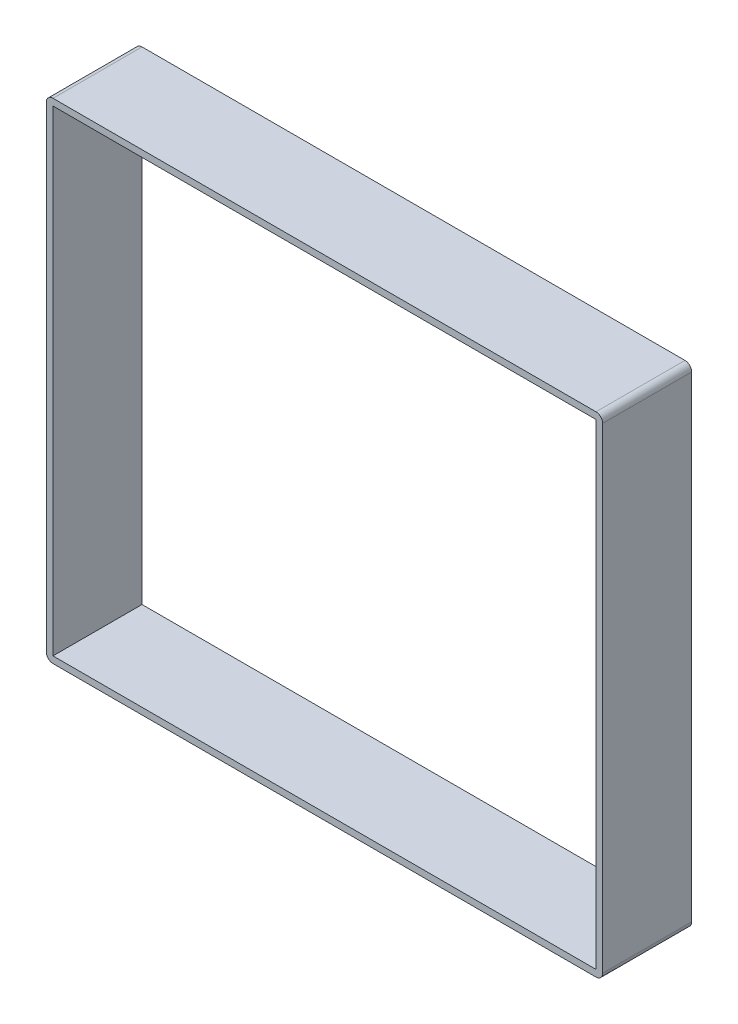
SolidWorks part; units mm, degrees
ref_plane "Top plane" through (0, 0, 0) normal (0, 0, 1) x (1, 0, 0)
ref_plane "Right plane" through (0, 0, 0) normal (0, 1, 0) x (1, 0, 0)
ref_plane "Front plane" through (0, 0, 0) normal (1, 0, 0) x (0, 0, -1)
sketch "Sketch1" plane through (0, 0, 0) normal (0, 0, 1) x (1, 0, 0)
  line L1 (160.4612, -30.1451) -> (-89.5388, -30.1451)
  line L2 (160.4612, -30.1451) -> (160.4612, 189.8549)
  line L3 (160.4612, 189.8549) -> (-89.5388, 189.8549)
  line L4 (-89.5388, -30.1451) -> (-89.5388, 189.8549)
extrude "Extrude-Thin1" add sketch "Sketch1" along normal blind 40 thin
fillet "Fillet1" radius 3 4 edges at (160.4612, 189.8549, 20) (-89.5388, 189.8549, 20) (-89.5388, -30.1451, 20) (160.4612, -30.1451, 20)
